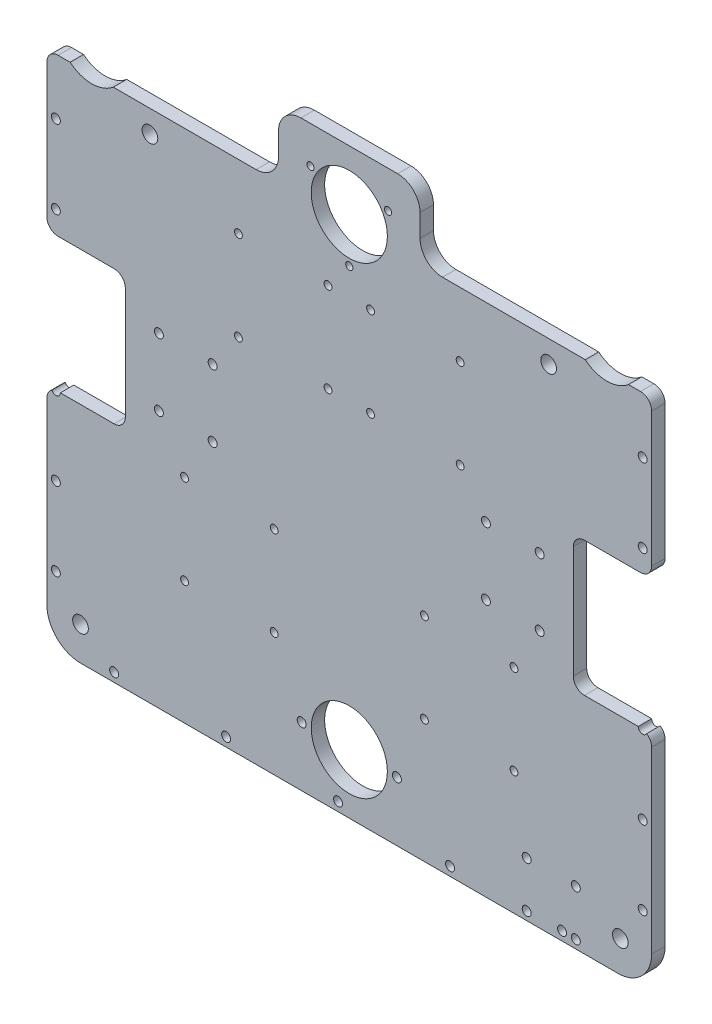
SolidWorks part; units mm, degrees
material "Alumina"
ref_plane "Front Plane" through (0, 0, 0) normal (0, 0, 1) x (1, 0, 0)
ref_plane "Top Plane" through (0, 0, 0) normal (0, 1, 0) x (1, 0, 0)
ref_plane "Right Plane" through (0, 0, 0) normal (1, 0, 0) x (0, 0, -1)
sketch "Sketch1" plane through (0, 0, 0) normal (0, 0, 1) x (1, 0, 0)
  line L1 (-135, 130) -> (135, 130)
  line L2 (-135, 130) -> (-135, -130)
  line L3 (-135, -130) -> (135, -130)
  line L4 (135, 130) -> (135, -130)
  line L5 (-135, 130) -> (135, -130) construction
  line L6 (-135, -130) -> (135, 130) construction
  point P0 (0, 0)
  dimension "D1" = 270
  dimension "D2" = 260
extrude "Boss-Extrude1" add sketch "Sketch1" along normal blind 6
sketch "Sketch2" plane through (0, 0, 6) normal (0, 0, 1) x (1, 0, 0)
  line L0 (-135, 130) -> (-135, -130) construction
  line L1 (-135, 30) -> (-100, 30)
  line L2 (-135, 30) -> (-135, -30)
  line L3 (-135, -30) -> (-100, -30)
  line L4 (-100, 30) -> (-100, -30)
  line L5 (-135, 30) -> (-100, -30) construction
  line L6 (-135, -30) -> (-100, 30) construction
  circle A0 centre (-85, 15) radius 2
  circle A1 centre (-61, 15) radius 2
  circle A2 centre (-61, -15) radius 2
  circle A3 centre (-85, -15) radius 2
  point P0 (-117.5, 0)
  dimension "D3" = 4
  dimension "D4" = 24
  dimension "D5" = 30
  dimension "D6" = 50
  dimension "D1" = 35
  dimension "D2" = 60
extrude "Cut-Extrude1" cut sketch "Sketch2" against normal through all
sketch "Sketch3" plane through (0, 0, 6) normal (0, 0, 1) x (1, 0, 0)
  line L1 (0, -103.5) -> (0, -83.5) construction
  line L2 (0, -103.5) -> (17.3205, -113.5) construction
  line L3 (0, -103.5) -> (-17.3205, -113.5) construction
  circle A3 centre (0, -103.5) radius 17
  dimension "D2" = 34
  dimension "D4" = 120
  dimension "D5" = 120
  dimension "D6" = 20
extrude "Cut-Extrude2" cut sketch "Sketch3" against normal through all
mirror "Mirror1" about plane through (0, 0, 0) normal (1, 0, 0) of "Cut-Extrude1"
mirror "Mirror2" about plane through (0, 0, 0) normal (0, 1, 0) of "Cut-Extrude2"
sketch "Sketch4" plane through (0, 0, 6) normal (0, 0, 1) x (1, 0, 0)
  circle A0 centre (21.25, -103.5) radius 2
  circle A1 centre (-21.25, -103.5) radius 2
  dimension "D1" = 4
extrude "Cut-Extrude3" cut sketch "Sketch4" against normal through all
sketch "Sketch5" plane through (0, 0, 6) normal (0, 0, 1) x (1, 0, 0)
  circle A0 centre (79.2065, -126.2348) radius 2
  circle A1 centre (79.2065, -105.7652) radius 2
  circle A2 centre (101.1382, -105.7652) radius 2
  circle A3 centre (101.1382, -126.2348) radius 2
  dimension "D1" = 4
extrude "Cut-Extrude4" cut sketch "Sketch5" against normal through all
fillet "Fillet1" radius 15 4 edges at (135, 130, 3) (-135, 130, 3) (-135, -130, 3) (135, -130, 3)
sketch "Sketch6" plane through (0, 0, 6) normal (0, 0, 1) x (1, 0, 0)
  circle A0 centre (-115, 115) radius 12.5
  dimension "D1" = 25
extrude "Cut-Extrude5" cut sketch "Sketch6" against normal through all
sketch "Sketch7" plane through (0, 0, 6) normal (0, 0, 1) x (1, 0, 0)
  line L3 (-95.6553, 110.7637) -> (-27.9414, 110.7637)
  line L4 (-27.9414, 110.7637) -> (-27.9414, 130)
  line L5 (120, 130) -> (-120, 130) construction
sketch "Sketch8" plane through (0, 0, 6) normal (0, 0, 1) x (1, 0, 0)
  circle A0 centre (49.5, 31.3) radius 1.75
  circle A1 centre (9.5, 31.3) radius 1.75
  circle A2 centre (9.5, 71.3) radius 1.75
  circle A3 centre (49.5, 71.3) radius 1.75
  circle A4 centre (-49.5, 31.3) radius 1.75
  circle A5 centre (-9.5, 31.3) radius 1.75
  circle A6 centre (-49.5, 71.3) radius 1.75
  circle A7 centre (-9.5, 71.3) radius 1.75
  dimension "D1" = 3.5
extrude "Cut-Extrude6" cut sketch "Sketch8" against normal through all
sketch "Sketch9" plane through (0, 0, 6) normal (0, 0, 1) x (1, 0, 0)
  circle A0 centre (115, 111.5) radius 12.5
  dimension "D1" = 25
extrude "Cut-Extrude7" cut sketch "Sketch9" against normal through all
sketch "Sketch10" plane through (0, 0, 6) normal (0, 0, 1) x (1, 0, 0)
  line L0 (135, 30) -> (135, 115) construction
  line L1 (135, 100) -> (31.5934, 100)
  line L2 (135, 100) -> (135, 130)
  line L3 (135, 130) -> (31.5934, 130)
  line L4 (31.5934, 100) -> (31.5934, 130)
  line L5 (120, 130) -> (-120, 130) construction
  dimension "D1" = 30
extrude "Cut-Extrude8" cut sketch "Sketch10" against normal through all
ref_plane "Plane1" through (0, 0, 0) normal (-1, 0, 0) x (0, 0, 1)
fillet "Fillet2" radius 10 2 edges at (31.5934, 130, 3) (31.5934, 100, 3)
mirror "Mirror3" about plane through (0, 0, 0) normal (-1, 0, 0) of "Cut-Extrude8", "Fillet2"
sketch "Sketch11" plane through (0, 0, 6) normal (0, 0, 1) x (1, 0, 0)
  circle A0 centre (-17.3205, 113.5) radius 1.6
  circle A1 centre (17.3205, 113.5) radius 1.6
  circle A2 centre (0, 83.5) radius 1.6
  circle A3 centre (89, 90) radius 3.5
  circle A4 centre (-89, 90) radius 3.5
  circle A5 centre (121, -116) radius 3.5
  circle A6 centre (-120, -115) radius 3.5
  dimension "D1" = 3.2
  dimension "D2" = 7
extrude "Cut-Extrude9" cut sketch "Sketch11" against normal through all
sketch "Sketch12" plane through (0, 0, 6) normal (0, 0, 1) x (1, 0, 0)
  circle A0 centre (115, 111.5) radius 15
  circle A1 centre (-115, 111.5) radius 15
  dimension "D1" = 30
  dimension "D2" = 30
extrude "Cut-Extrude10" cut sketch "Sketch12" against normal through all
fillet "Fillet3" radius 5 2 edges at (135, 100, 3) (-135, 100, 3)
fillet "Fillet4" radius 5 8 edges at (135, 30, 3) (100, 30, 3) (100, -30, 3) (135, -30, 3) (-135, -30, 3) (-100, -30, 3) (-100, 30, 3) (-135, 30, 3)
sketch "Sketch13" plane through (0, 0, 6) normal (0, 0, 1) x (1, 0, 0)
  line L0 (0, 2.2) -> (0, -2.2) construction
  line L1 (-120, -130) -> (120, -130) construction
  line L2 (-135, -35) -> (-135, -115) construction
  circle A0 centre (33.5446, -34.9403) radius 1.75
  circle A1 centre (73.5446, -34.9403) radius 1.75
  circle A2 centre (73.5446, -74.9403) radius 1.75
  circle A3 centre (33.5446, -74.9403) radius 1.75
  circle A4 centre (-33.5446, -74.9403) radius 1.75
  circle A5 centre (-73.5446, -74.9403) radius 1.75
  circle A6 centre (-73.5446, -34.9403) radius 1.75
  circle A7 centre (-33.5446, -34.9403) radius 1.75
  circle A8 centre (-131, -100) radius 2
  circle A9 centre (-131, -65) radius 2
  circle A10 centre (-131, -30) radius 2
  circle A11 centre (-131, 5) radius 2
  circle A12 centre (-131, 40) radius 2
  circle A13 centre (-131, 75) radius 2
  circle A14 centre (-105, -126) radius 2
  circle A15 centre (-55, -126) radius 2
  circle A16 centre (-5, -126) radius 2
  circle A17 centre (45, -126) radius 2
  circle A18 centre (95, -126) radius 2
  circle A19 centre (145, -126) radius 2
  circle A20 centre (195, -126) radius 2
  circle A21 centre (245, -126) radius 2
  circle A22 centre (295, -126) radius 2
  circle A23 centre (345, -126) radius 2
  circle A24 centre (395, -126) radius 2
  circle A25 centre (445, -126) radius 2
  circle A26 centre (495, -126) radius 2
  circle A28 centre (131, 75) radius 2
  circle A29 centre (131, 40) radius 2
  circle A30 centre (131, 5) radius 2
  circle A31 centre (131, -30) radius 2
  circle A32 centre (131, -65) radius 2
  circle A33 centre (131, -100) radius 2
  dimension "D1" = 3.5
  dimension "D5" = 30
  dimension "D6" = 4
  dimension "D9" = 4
  dimension "D2" = 40
  dimension "D3" = 40
  dimension "D4" = 40
  dimension "D7" = 4
  dimension "D10" = 4
  dimension "D11" = 30
  dimension "D8" = 6
  dimension "D12" = 13
extrude "Cut-Extrude11" cut sketch "Sketch13" against normal through all
